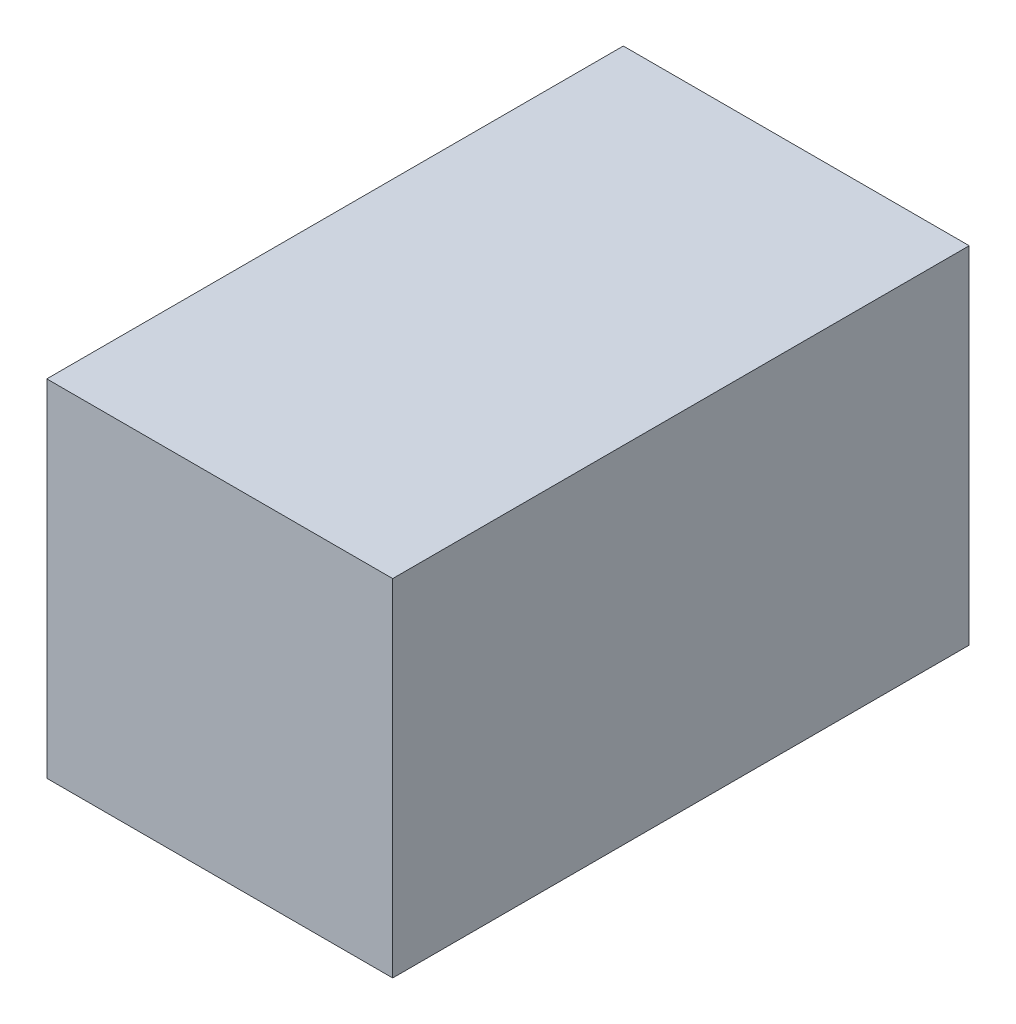
SolidWorks part; units mm, degrees
ref_plane "Front Plane" through (0, 0, 0) normal (0, 0, 1) x (1, 0, 0)
ref_plane "Top Plane" through (0, 0, 0) normal (0, 1, 0) x (1, 0, 0)
ref_plane "Right Plane" through (0, 0, 0) normal (1, 0, 0) x (0, 0, -1)
sketch "Sketch1" plane through (0, 0, 0) normal (0, 0, 1) x (1, 0, 0)
  line L1 (7.5, -7.5) -> (-7.5, -7.5)
  line L2 (7.5, -7.5) -> (7.5, 7.5)
  line L3 (7.5, 7.5) -> (-7.5, 7.5)
  line L4 (-7.5, -7.5) -> (-7.5, 7.5)
  line L5 (7.5, -7.5) -> (-7.5, 7.5) construction
  line L6 (7.5, 7.5) -> (-7.5, -7.5) construction
  point P0 (0, 0)
  dimension "D1" = 15
  dimension "D2" = 15
extrude "Boss-Extrude1" add sketch "Sketch1" along normal blind 25
